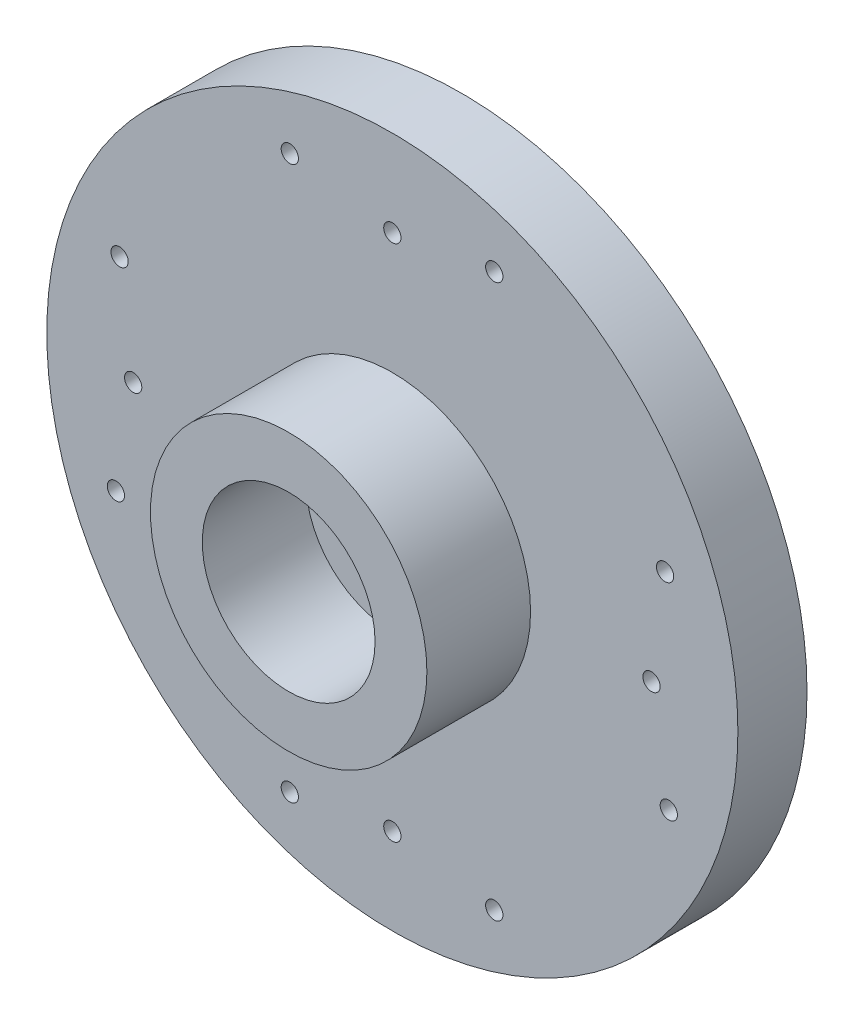
SolidWorks part; units mm, degrees
ref_plane "Plan de face" through (0, 0, 0) normal (0, 0, 1) x (1, 0, 0)
ref_plane "Plan de dessus" through (0, 0, 0) normal (0, 1, 0) x (1, 0, 0)
ref_plane "Plan de droite" through (0, 0, 0) normal (1, 0, 0) x (0, 0, -1)
sketch "Esquisse1" plane through (0, 0, 0) normal (0, 0, 1) x (1, 0, 0)
  circle A0 centre (0, 0) radius 1.2
  circle A1 centre (0, 0) radius 12
  dimension "D1" = 24
  dimension "D2" = 2.4
extrude "Boss.-Extru.2" add sketch "Esquisse1" along normal blind 2.4
sketch "Esquisse3" plane through (0, 0, 2.4) normal (0, 0, 1) x (1, 0, 0)
  circle A0 centre (0, 0) radius 4.8
  circle A1 centre (0, 0) radius 3
  dimension "D1" = 9.6
  dimension "D2" = 6
extrude "Boss.-Extru.3" add sketch "Esquisse3" along normal blind 3.6
sketch "Esquisse4" plane through (0, 0, 2.4) normal (0, 0, 1) x (1, 0, 0)
  line L0 (0, 15.1238) -> (0, -14.7833) construction
  line L1 (-15.294, 0) -> (14.6698, 0) construction
  line L2 (0, 0) -> (-9.6, -3.5607)
  line L3 (0, 0) -> (-3.5607, 9.6)
  circle A0 centre (-9, 0) radius 0.3
  circle A1 centre (-9.4712, 3.5422) radius 0.3
  circle A2 centre (-9.6, -3.5607) radius 0.3
  circle A3 centre (0, 9) radius 0.3
  circle A4 centre (-3.5607, 9.6) radius 0.3
  circle A5 centre (3.5393, 9.6) radius 0.3
  circle A6 centre (9.6, -3.5607) radius 0.3
  circle A7 centre (9, 0) radius 0.3
  circle A8 centre (9.4712, 3.5422) radius 0.3
  circle A9 centre (3.5393, -9.6) radius 0.3
  circle A10 centre (0, -9) radius 0.3
  circle A11 centre (-3.5607, -9.6) radius 0.3
  point P30 (0, 0)
  dimension "D1" = 0.6
  dimension "D2" = 0.6
  dimension "D3" = 0.6
  dimension "D4" = 0.6
  dimension "D5" = 0.6
  dimension "D6" = 0.6
  dimension "D7" = 7.104
  dimension "D8" = 90
  dimension "D9" = 7.1
  dimension "D10" = 9
  dimension "D11" = 9
  dimension "D12" = 9.6
  dimension "D13" = 9.6
  dimension "D14" = 9.6
  dimension "D15" = 20.35
extrude "Enlèv. mat.-Extru.1" cut sketch "Esquisse4" against normal blind 3.6
sketch "Esquisse5" plane through (0, 0, 0) normal (0, 0, -1) x (-1, 0, 0)
  circle A0 centre (0, 0) radius 3.6
  dimension "D1" = 7.2
extrude "Enlèv. mat.-Extru.2" cut sketch "Esquisse5" against normal blind 0.6 contours A0
